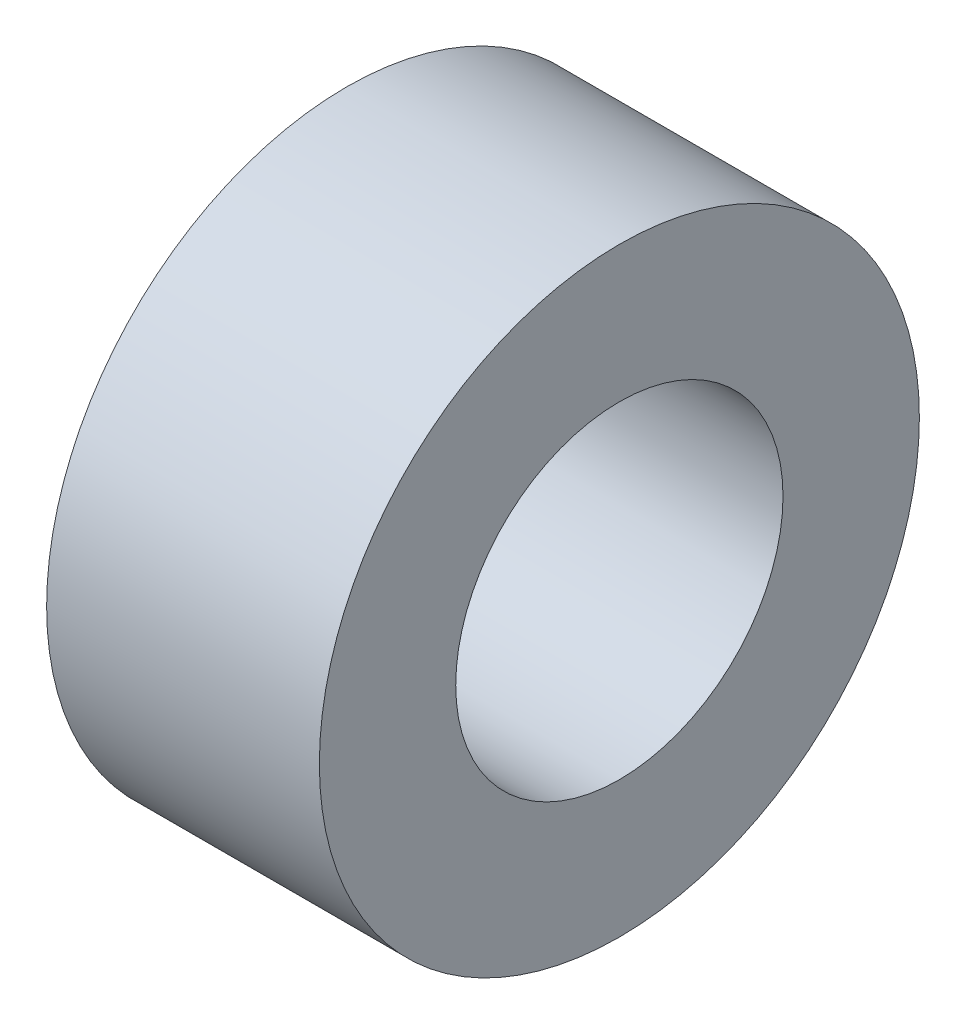
SolidWorks part; units mm, degrees
ref_plane "前视基准面" through (0, 0, 0) normal (0, 0, 1) x (1, 0, 0)
ref_plane "上视基准面" through (0, 0, 0) normal (0, 1, 0) x (1, 0, 0)
ref_plane "右视基准面" through (0, 0, 0) normal (1, 0, 0) x (0, 0, -1)
sketch "草图1" plane through (0, 0, 0) normal (1, 0, 0) x (0, 0, -1)
  circle A0 centre (0, 0) radius 3
  circle A1 centre (0, 0) radius 5.5
  dimension "D1" = 11
  dimension "D2" = 6
extrude "凸台-拉伸1" add sketch "草图1" along normal blind 5
